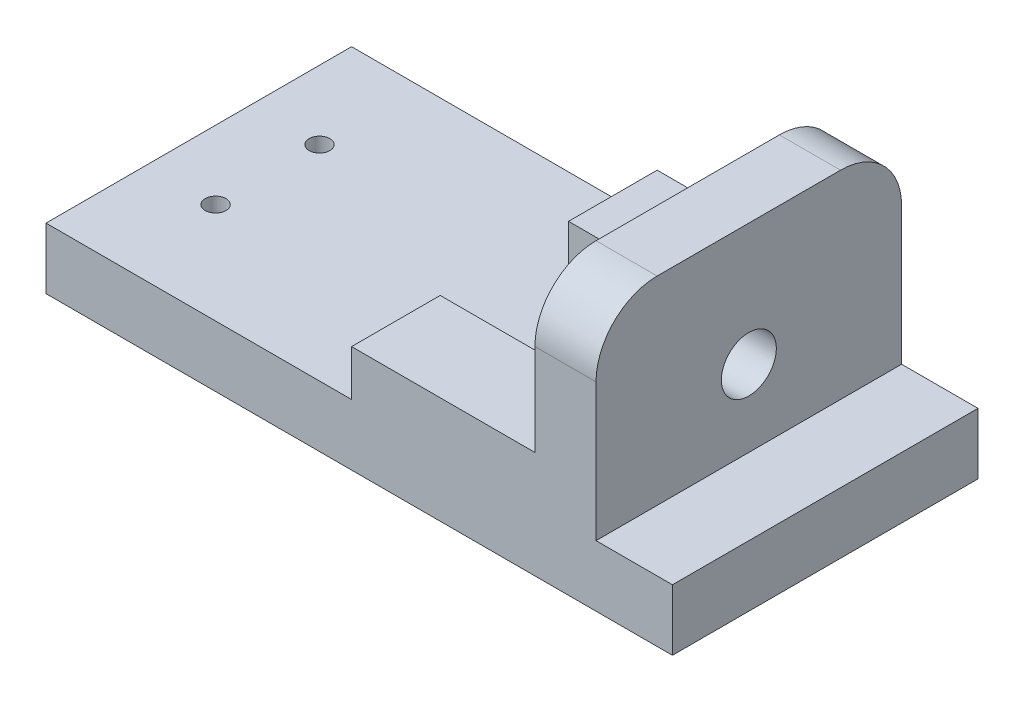
SolidWorks part; units mm, degrees
ref_plane "Front Plane" through (0, 0, 0) normal (0, 0, 1) x (1, 0, 0)
ref_plane "Top Plane" through (0, 0, 0) normal (0, 1, 0) x (1, 0, 0)
ref_plane "Right Plane" through (0, 0, 0) normal (1, 0, 0) x (0, 0, -1)
sketch "Sketch1" plane through (0, 0, 0) normal (0, 1, 0) x (1, 0, 0)
  line L1 (0, 0) -> (205, 0)
  line L2 (0, 0) -> (0, 100)
  line L3 (0, 100) -> (205, 100)
  line L4 (205, 0) -> (205, 100)
  dimension "D1" = 205
  dimension "D2" = 100
extrude "Boss-Extrude1" add sketch "Sketch1" along normal blind 20
sketch "Sketch2" plane through (0, 20, 0) normal (0, 1, 0) x (1, 0, 0)
  line L0 (22.5, 33) -> (22.5, 67)
  line L1 (0, 0) -> (22.5, 0)
  line L2 (0, 0) -> (0, 33)
  line L3 (0, 33) -> (22.5, 33)
  line L4 (22.5, 0) -> (22.5, 33)
  point P5 (22.5, 33)
  point P8 (22.5, 67)
  dimension "D1" = 22.5
  dimension "D2" = 33
  dimension "D3" = 34
hole_wizard "M8 Tapped Hole1" positions "3DSketch1" profile "Sketch3" tap size "M8" standard "ISO" end condition through all
sketch3d "3DSketch1"
  point P0 (22.5, 20, -33)
  point P3 (22.5, 20, -67)
sketch "Sketch3" plane through (22.5, 20, -33) normal (1, 0, 0) x (0, 0, 1)
  line L0 (0, 0) -> (0, 20)
  line L1 (0, 20) -> (3.4, 20)
  line L2 (3.4, 20) -> (3.4, 0)
  line L5 (3.4, 0) -> (0, 0)
  line L11 (0, -6.35) -> (0, 107.95) construction
  dimension "Thru Tap Drill Dia." = 6.8
  dimension "Thru Tap Drill Depth" = 20
cosmetic thread "Hole Thread1" parameters "D2"=8
cosmetic thread "Hole Thread2" parameters "D2"=8
sketch "Sketch11" plane through (0, 20, 0) normal (0, 1, 0) x (1, 0, 0)
  line L0 (205, 0) -> (180, 0)
  line L1 (0, 0) -> (205, 0) construction
  line L2 (205, 100) -> (0, 100) construction
  line L3 (180, 0) -> (160, 0)
  line L4 (180, 0) -> (180, 100)
  line L5 (180, 100) -> (160, 100)
  line L6 (160, 0) -> (160, 100)
  line M9 (0, 0) -> (205, 0)
  line M11 (205, 100) -> (0, 100)
  dimension "D1" = 25
  dimension "D2" = 20
extrude "Boss-Extrude4" add sketch "Sketch11" along normal blind 65 contours L6 L4 M9 M11
sketch "Sketch12" plane through (0, 20, 0) normal (0, 1, 0) x (1, 0, 0)
  line L1 (160, 0) -> (100, 0)
  line L2 (160, 0) -> (160, 29)
  line L3 (160, 29) -> (100, 29)
  line L4 (100, 0) -> (100, 29)
  line L5 (160, 100) -> (100, 100)
  line L6 (160, 100) -> (160, 71)
  line L7 (160, 71) -> (100, 71)
  line L8 (100, 100) -> (100, 71)
  dimension "D1" = 60
  dimension "D2" = 29
  dimension "D3" = 60
  dimension "D4" = 29
extrude "Boss-Extrude5" add sketch "Sketch12" along normal blind 15
fillet "Fillet2" radius 20 2 edges at (170, 85, 0) (170, 85, -100)
hole_wizard "Ø18.0 (18) Diameter Hole2" positions "Sketch14" profile "Sketch15" hole size "Ø18.0" standard "ISO" end condition through all
sketch "Sketch14" plane through (160, 0, 0) normal (-1, 0, 0) x (0, 0, 1)
  line L0 (-50, 20) -> (-50, 45)
  line L1 (-29, 20) -> (-71, 20) construction
  point P2 (-50, 45)
sketch "Sketch15" plane through (160, 45, -50) normal (0, 1, 0) x (0, 0, 1)
  line L0 (0, 0) -> (0, 45)
  line L1 (0, 45) -> (9, 45)
  line L2 (9, 45) -> (9, 0)
  line L5 (9, 0) -> (0, 0)
  line L11 (0, -6.35) -> (0, 107.95) construction
  dimension "Thru Hole Dia." = 18
  dimension "Thru Hole Depth" = 45
